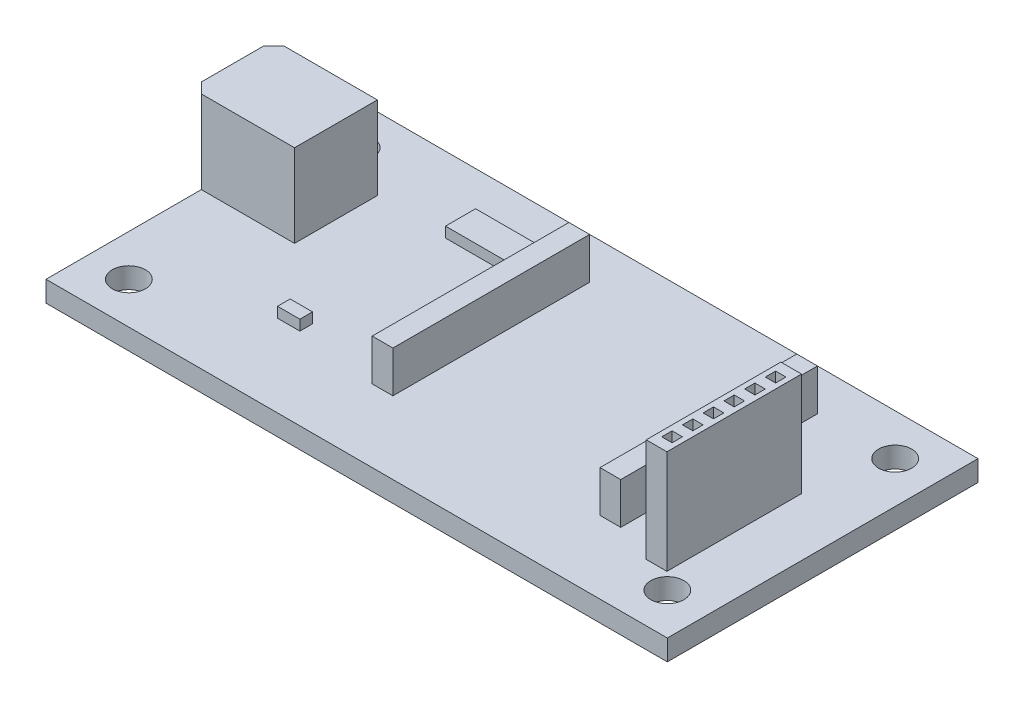
SolidWorks part; units mm, degrees
ref_plane "Front" through (0, 0, 0) normal (0, 0, 1) x (1, 0, 0)
ref_plane "Top" through (0, 0, 0) normal (0, 1, 0) x (1, 0, 0)
ref_plane "Right" through (0, 0, 0) normal (1, 0, 0) x (0, 0, -1)
sketch "Sketch1" plane through (0, 0, 0) normal (0, 1, 0) x (1, 0, 0)
  line L0 (0, 30) -> (0, 0)
  line L1 (0, 0) -> (60, 0)
  line L3 (0, 30) -> (60, 30)
  line L4 (60, 0) -> (60, 30)
  circle A0 centre (4, 4) radius 1.6
  circle A1 centre (4, 26) radius 1.6
  circle A2 centre (56, 26) radius 1.6
  circle A3 centre (56, 4) radius 1.6
extrude "Boss-Extrude1" add sketch "Sketch1" along normal blind 2
sketch "Sketch2" plane through (0, 2, 0) normal (0, 1, 0) x (1, 0, 0)
  line L0 (24.5, 26) -> (26.5, 26)
  line L1 (24.5, 26) -> (24.5, 7)
  line L2 (24.5, 7) -> (26.5, 7)
  line L3 (26.5, 26) -> (26.5, 7)
  line L4 (46.5, 26) -> (46.5, 7)
  line L5 (48.5, 7) -> (46.5, 7)
  line L6 (48.5, 26) -> (48.5, 7)
  line L7 (48.5, 26) -> (46.5, 26)
extrude "Boss-Extrude2" add sketch "Sketch2" along normal blind 4
sketch "Sketch3" plane through (0, 2, 0) normal (0, 1, 0) x (1, 0, 0)
  line L1 (54.4052, 5.5533) -> (52.4052, 5.5533)
  line L2 (54.4052, 5.5533) -> (54.4052, 18.5533)
  line L3 (54.4052, 18.5533) -> (52.4052, 18.5533)
  line L4 (52.4052, 5.5533) -> (52.4052, 18.5533)
extrude "Boss-Extrude3" add sketch "Sketch3" along normal blind 10
sketch "Sketch4" plane through (0, 2, 0) normal (0, 1, 0) x (1, 0, 0)
  line L1 (15.843, 25.6412) -> (21.7496, 25.6412)
  line L2 (15.843, 25.6412) -> (15.843, 22.7348)
  line L3 (15.843, 22.7348) -> (21.7496, 22.7348)
  line L4 (21.7496, 25.6412) -> (21.7496, 22.7348)
  line L5 (14.4367, 9.1403) -> (16.593, 9.1403)
  line L6 (14.4367, 9.1403) -> (14.4367, 7.9215)
  line L7 (14.4367, 7.9215) -> (16.593, 7.9215)
  line L8 (16.593, 9.1403) -> (16.593, 7.9215)
extrude "Boss-Extrude4" add sketch "Sketch4" along normal blind 1
sketch "Sketch6" plane through (0, 2, 0) normal (0, 1, 0) x (1, 0, 0)
  line L1 (9, 23) -> (9, 15)
  line L2 (9, 23) -> (0, 23)
  line L3 (-1, 22) -> (-1, 16)
  line L4 (9, 15) -> (0, 15)
  line L14 (0, 23) -> (-1, 22)
  line L15 (0, 15) -> (-1, 16)
extrude "Boss-Extrude5" add sketch "Sketch6" along normal blind 8
sketch "Sketch7" plane through (-1, 0, 0) normal (-1, 0, 0) x (0, 0, 1)
  line L0 (-20.5, 9.25) -> (-17.5, 9.25)
  line L1 (-20.5, 9.25) -> (-20.5, 6.25)
  line L2 (-20.5, 6.25) -> (-17.5, 6.25)
  line L3 (-17.5, 9.25) -> (-17.5, 6.25)
  line L4 (-20.5, 5.75) -> (-20.5, 2.75)
  line L5 (-20.5, 5.75) -> (-17.5, 5.75)
  line L6 (-17.5, 5.75) -> (-17.5, 2.75)
  line L7 (-20.5, 2.75) -> (-17.5, 2.75)
extrude "Cut-Extrude1" cut sketch "Sketch7" against normal blind 9
sketch "Sketch9" plane through (0, 12, 0) normal (0, 1, 0) x (1, 0, 0)
  line L0 (52.9052, 13.5533) -> (53.9052, 13.5533)
  line L1 (52.9052, 17.5533) -> (53.9052, 17.5533)
  line L2 (52.9052, 17.5533) -> (52.9052, 16.5533)
  line L3 (52.9052, 16.5533) -> (53.9052, 16.5533)
  line L4 (53.9052, 17.5533) -> (53.9052, 16.5533)
  line L6 (52.9052, 15.5533) -> (53.9052, 15.5533)
  line L8 (52.9052, 15.5533) -> (52.9052, 14.5533)
  line L9 (52.9052, 14.5533) -> (53.9052, 14.5533)
  line L10 (53.9052, 15.5533) -> (53.9052, 14.5533)
  line L11 (52.9052, 12.5533) -> (53.9052, 12.5533)
  line L12 (52.9052, 13.5533) -> (52.9052, 12.5533)
  line L13 (53.9052, 13.5533) -> (53.9052, 12.5533)
  line L14 (52.9052, 11.5533) -> (52.9052, 10.5533)
  line L15 (52.9052, 10.5533) -> (53.9052, 10.5533)
  line L16 (52.9052, 9.5533) -> (52.9052, 8.5533)
  line L17 (52.9052, 9.5533) -> (53.9052, 9.5533)
  line L19 (52.9052, 11.5533) -> (53.9052, 11.5533)
  line L20 (53.9052, 9.5533) -> (53.9052, 8.5533)
  line L22 (53.9052, 11.5533) -> (53.9052, 10.5533)
  line L23 (52.9052, 8.5533) -> (53.9052, 8.5533)
  line L24 (52.9052, 6.5533) -> (53.9052, 6.5533)
  line L25 (52.9052, 7.5533) -> (53.9052, 7.5533)
  line L27 (52.9052, 7.5533) -> (52.9052, 6.5533)
  line L28 (53.9052, 7.5533) -> (53.9052, 6.5533)
extrude "Cut-Extrude2" cut sketch "Sketch9" against normal blind 9
